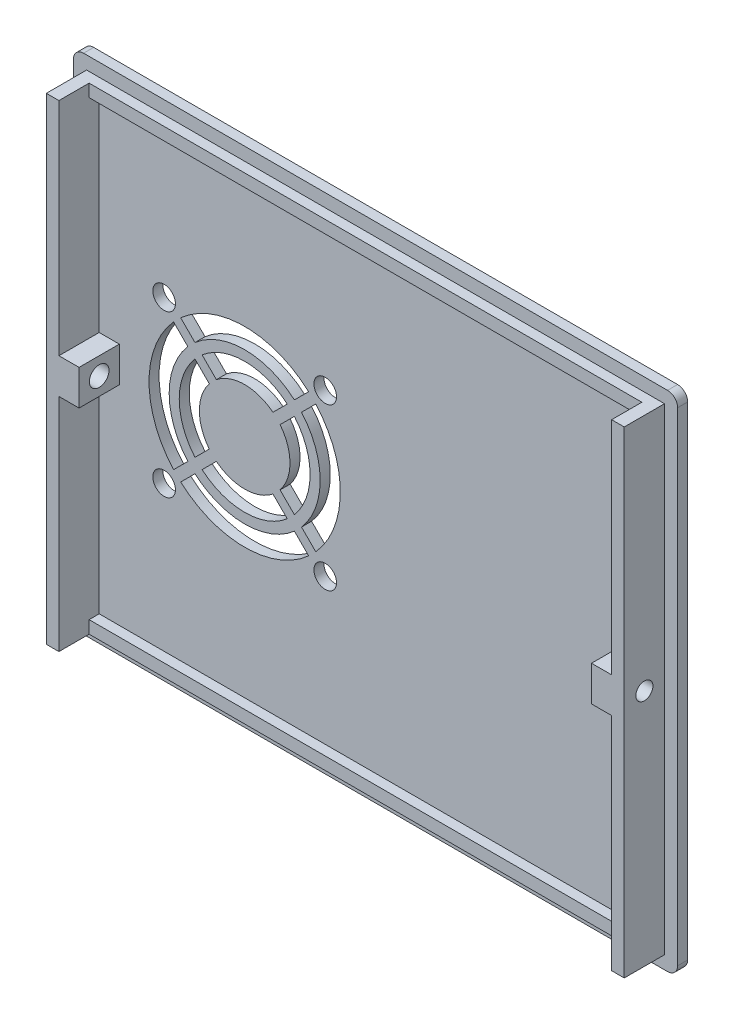
SolidWorks part; units mm, degrees
ref_plane "Přední rovina" through (0, 0, 0) normal (0, 0, 1) x (1, 0, 0)
ref_plane "Horní rovina" through (0, 0, 0) normal (0, 1, 0) x (1, 0, 0)
ref_plane "Pravá rovina" through (0, 0, 0) normal (1, 0, 0) x (0, 0, -1)
sketch "půdorys" plane through (0, 0, 0) normal (0, 0, 1) x (1, 0, 0)
  line L1 (-60, 50) -> (60, 50)
  line L2 (-60, 50) -> (-60, -50)
  line L3 (-60, -50) -> (60, -50)
  line L4 (60, 50) -> (60, -50)
  line L5 (-60, 50) -> (60, -50) construction
  line L6 (-60, -50) -> (60, 50) construction
  point P0 (0, 0)
  dimension "D1" = 120
  dimension "D2" = 100
extrude "Přidat vysunutím1" add sketch "půdorys" along normal blind 2
fillet "Zaoblit1" radius 2 4 edges at (-60, 50, 1) (-60, -50, 1) (60, -50, 1) (60, 50, 1)
sketch "Skica2" plane through (0, 0, 2) normal (0, 0, 1) x (1, 0, 0)
  line L0 (54.9, -44.9) -> (54.9, 44.9)
  line L1 (57.4, -47.4) -> (-57.4, -47.4)
  line L2 (57.4, -47.4) -> (57.4, 47.4)
  line L3 (57.4, 47.4) -> (-57.4, 47.4)
  line L4 (-57.4, -47.4) -> (-57.4, 47.4)
  line L5 (57.4, -47.4) -> (-57.4, 47.4) construction
  line L6 (57.4, 47.4) -> (-57.4, -47.4) construction
  line L7 (54.9, 44.9) -> (-54.9, 44.9)
  line L8 (-54.9, -44.9) -> (-54.9, 44.9)
  line L9 (54.9, -44.9) -> (-54.9, -44.9)
  line L10 (-54.9, 0) -> (0, 0)
  line L11 (0, 0) -> (0, -44.9)
  line L12 (-50.9, 3.5) -> (-54.9, 3.5)
  line L13 (-50.9, 3.5) -> (-50.9, -3.5)
  line L14 (-50.9, -3.5) -> (-54.9, -3.5)
  line L15 (-54.9, 3.5) -> (-54.9, -3.5)
  line L16 (-50.9, 3.5) -> (-54.9, -3.5) construction
  line L17 (-50.9, -3.5) -> (-54.9, 3.5) construction
  line L18 (50.9, -3.5) -> (54.9, -3.5)
  line L19 (50.9, 3.5) -> (50.9, -3.5)
  line L20 (50.9, 3.5) -> (54.9, 3.5)
  point P0 (0, 0)
  point P14 (-52.9, 0)
  dimension "D1" = 2.6
  dimension "D2" = 2.6
  dimension "D4" = 7
  dimension "D5" = 4
  dimension "D3" = 2.5
extrude "Přidat vysunutím2" add sketch "Skica2" along normal blind 2 contours L4 L1 L2 L3 L0 L9 L8 L7 | L20 L19 L18 L0 | L14 L13 L10 L8 | L13 L12 L8 L10
sketch "Skica3" plane through (0, 0, 4) normal (0, 0, 1) x (1, 0, 0)
  line L0 (57.4, -47.4) -> (57.4, 47.4)
  line L1 (57.4, 47.4) -> (-57.4, 47.4) construction
  line L2 (57.4, -47.4) -> (57.4, 47.4) construction
  line L3 (57.4, 47.4) -> (54.9, 47.4)
  line L4 (54.9, 47.4) -> (54.9, 3.5)
  line L5 (54.9, 3.5) -> (50.9, 3.5)
  line L6 (50.9, 3.5) -> (54.9, 3.5) construction
  line L7 (50.9, 3.5) -> (50.9, -3.5) construction
  line L8 (50.9, 3.5) -> (50.9, -3.5)
  line L9 (50.9, -3.5) -> (54.9, -3.5)
  line L10 (54.9, -3.5) -> (54.9, -47.4)
  line L11 (57.4, -47.4) -> (-57.4, -47.4) construction
  line L12 (54.9, -47.4) -> (57.4, -47.4)
  line L13 (0, -44.9) -> (0, 47.4)
  line L14 (54.9, -44.9) -> (-54.9, -44.9) construction
  line L15 (-54.9, -47.4) -> (-57.4, -47.4)
  line L16 (-54.9, -3.5) -> (-54.9, -47.4)
  line L17 (-50.9, -3.5) -> (-54.9, -3.5)
  line L18 (-50.9, 3.5) -> (-50.9, -3.5)
  line L19 (-54.9, 3.5) -> (-50.9, 3.5)
  line L20 (-54.9, 47.4) -> (-54.9, 3.5)
  line L21 (-57.4, -47.4) -> (-57.4, 47.4)
  line L22 (-57.4, 47.4) -> (-54.9, 47.4)
  line M2 (-50.9, -3.5) -> (-50.9, 3.5)
  line M3 (-50.9, 3.5) -> (-54.9, 3.5)
  line M4 (-54.9, 3.5) -> (-54.9, 44.9)
  line M6 (54.9, 44.9) -> (54.9, 3.5)
  line M7 (54.9, 3.5) -> (50.9, 3.5)
  line M8 (50.9, 3.5) -> (50.9, -3.5)
  line M9 (50.9, -3.5) -> (54.9, -3.5)
  line M10 (54.9, -3.5) -> (54.9, -44.9)
  line M12 (-54.9, -44.9) -> (-54.9, -3.5)
  line M13 (-54.9, -3.5) -> (-50.9, -3.5)
  line M14 (-57.4, 47.4) -> (-57.4, -47.4)
  line M15 (-57.4, -47.4) -> (57.4, -47.4)
  line M16 (57.4, -47.4) -> (57.4, 47.4)
  line M17 (57.4, 47.4) -> (-57.4, 47.4)
extrude "Přidat vysunutím3" add sketch "Skica3" along normal blind 6 contours L10 L4 M10 M15 M16 M17 M6 M7 M8 M9 | L20 L16 M17 M14 M15 M12 M13 M2 M3 M4
sketch "Skica4" plane through (-50.9, 0, 0) normal (1, 0, 0) x (0, 0, -1)
  line L0 (-10, -3.5) -> (-2, 3.5)
  line L1 (-2, 3.5) -> (-10, 3.5)
  line L2 (-10, 3.5) -> (-2, -3.5)
  point P6 (-6, 0)
hole_wizard "Válcové zahloubení pro M6 šrouby s válcovou hlavou zaoblenou1" positions "3DSkica1" profile "Skica6" counterbore size "M6" standard "ANSI Metric"
sketch3d "3DSkica1"
  point P0 (-50.9, 0, 6)
sketch "Skica6" plane through (-50.9, 0, 6) normal (0, 1, 0) x (0, 0, -1)
  line L0 (0, 0) -> (0, 9.1)
  line L1 (0, 9.1) -> (1.7, 9.1)
  line L3 (1.7, 9.1) -> (1.7, 4)
  line L4 (1.7, 4) -> (1.95, 4)
  line L5 (1.95, 4) -> (1.95, 0)
  line L7 (1.95, 0) -> (0, 0)
  line L11 (0, -6.35) -> (0, 107.95) construction
  dimension "Průměr díry skrz" = 3.4
  dimension "Hloubka díry skrz" = 9.1
  dimension "Průměr válcového zahloubení" = 3.9
  dimension "Hloubka válcového zahloubení" = 4
ref_plane "Rovina1" through (0, 0, 0) normal (1, 0, 0) x (0, 0, -1)
mirror "Zrcadlit1" about plane through (0, 0, 0) normal (1, 0, 0) of "Válcové zahloubení pro M6 šrouby s válcovou hlavou zaoblenou1"
sketch "Skica7" plane through (0, 0, 0) normal (0, 0, -1) x (-1, 0, 0)
  line L0 (60, 0) -> (-60, 0)
  line L1 (60, 48) -> (60, -48) construction
  line L2 (-60, -48) -> (-60, 48) construction
  line L3 (42, -16) -> (10, 16)
  line L4 (42, -16) -> (10, -16)
  line L5 (42, -16) -> (42, 16)
  line L6 (42, 16) -> (10, 16)
  line L7 (10, -16) -> (10, 16)
  line L8 (42, -16) -> (10, 16) construction
  line L9 (42, 16) -> (10, -16) construction
  line L10 (42, 16) -> (10, -16)
  line L11 (42, 16) -> (41.2929, 16.7071)
  line L12 (10, -16) -> (10.714, -16.7001)
  line L13 (10, -16) -> (9.2929, -15.2929)
  line L14 (42, 16) -> (42.714, 15.2999)
  line L15 (10.714, -16.7001) -> (42.714, 15.2999)
  line L16 (41.2929, 16.7071) -> (9.2929, -15.2929)
  line L17 (42, -16) -> (42.7071, -15.2929)
  line L18 (42, -16) -> (41.2929, -16.7071)
  line L19 (10, 16) -> (13.6513, 19.6513)
  line L20 (10, 16) -> (5.7505, 11.7505)
  line L21 (41.2929, -16.7071) -> (9.2929, 15.2929)
  line L22 (42.7071, -15.2929) -> (10.7071, 16.7071)
  circle A0 centre (26, 0) radius 9
  circle A1 centre (42, -16) radius 2.25
  circle A2 centre (10, -16) radius 2.25
  circle A3 centre (10, 16) radius 2.25
  circle A4 centre (42, 16) radius 2.25
  circle A5 centre (26, 0) radius 13
  circle A6 centre (26, 0) radius 15
  circle A7 centre (26, 0) radius 19
  dimension "D2" = 18
  dimension "D5" = 4.5
  dimension "D1" = 34
  dimension "D3" = 32
  dimension "D4" = 32
  dimension "D9" = 1
  dimension "D10" = 1
  dimension "D11" = 1
  dimension "D6" = 4
  dimension "D7" = 2
  dimension "D8" = 4
extrude "Odebrat vysunutím1" cut sketch "Skica7" against normal blind 6 contours L4 A1 L5 L22 L17 L18 L21 | L22 A1 L3 L5 | L5 A1 L22 | L17 L22 L5 | L3 A1 L21 L4 | L21 L18 L4 | L21 A1 L4 | L7 A2 L4 L15 L12 L13 L16 | L4 A2 L15 | L12 L15 L4 | L7 L16 L13 | L10 A2 L16 L7 | L16 A2 L7 | L15 A2 L10 L4 | L19 A3 L20 | L6 A3 L19 L22 | L22 A3 L6 | L3 A3 L22 L6 | L6 L22 L19 | L21 L7 L20 | L21 A3 L3 L7 | L20 A3 L7 L21 | L7 A3 L21 | L5 A4 L6 L16 L11 L14 L15 | L6 A4 L16 | L16 A4 L10 L6 | L11 L16 L6 | L5 L15 L14 | L10 A4 L15 L5 | L15 A4 L5 | L6 A7 | L16 A7 L6 L22 A6 | L5 A7 L15 A6 L0 | L0 A7 L5 | L5 A7 L0 | L22 A7 L5 L0 A6 | L15 A7 L4 L21 A6 | L4 A7 | L7 A7 L16 A6 L0 | L0 A7 L7 | L7 A7 L0 | L21 A7 L7 L0 A6 | L0 A5 L15 A0 | L16 A5 L22 A0 | L21 A5 L0 A0 | L0 A5 L16 A0 | L15 A5 L21 A0 | L22 A5 L0 A0
